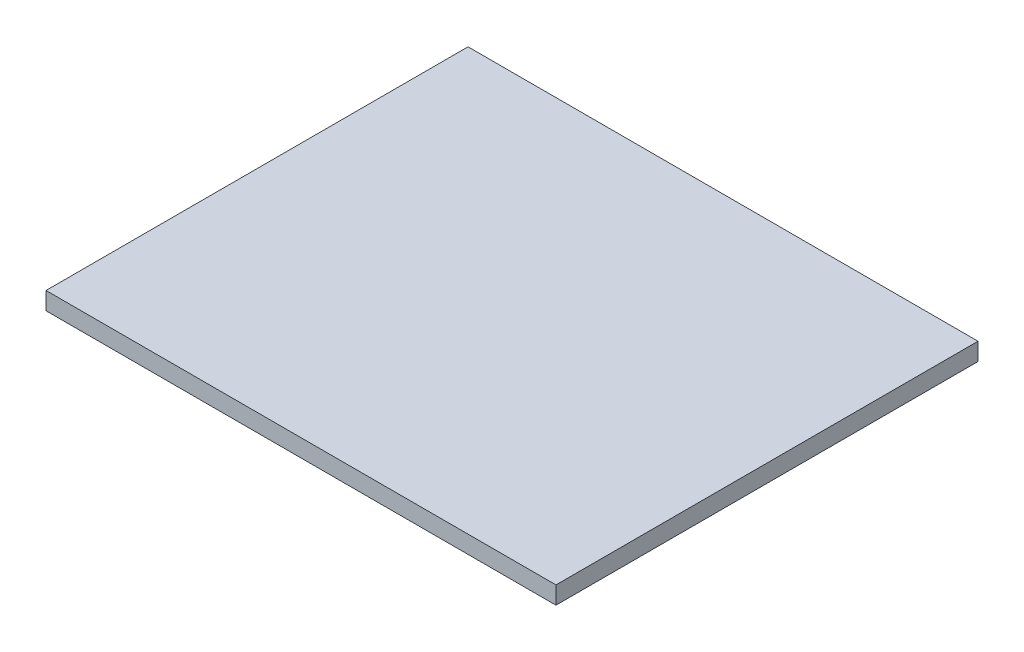
SolidWorks part; units mm, degrees
material "Ceramic Porcelain"
ref_plane "Front Plane" through (0, 0, 0) normal (0, 0, 1) x (1, 0, 0)
ref_plane "Top Plane" through (0, 0, 0) normal (0, 1, 0) x (1, 0, 0)
ref_plane "Right Plane" through (0, 0, 0) normal (1, 0, 0) x (0, 0, -1)
sketch "Sketch1" plane through (0, 0, 0) normal (0, 1, 0) x (1, 0, 0)
  line L1 (0, 0) -> (736.6, 0)
  line L2 (0, 0) -> (0, 609.6)
  line L3 (0, 609.6) -> (736.6, 609.6)
  line L4 (736.6, 0) -> (736.6, 609.6)
  dimension "D1" = 736.6
  dimension "D2" = 609.6
extrude "Boss-Extrude1" add sketch "Sketch1" along normal blind 25.4
